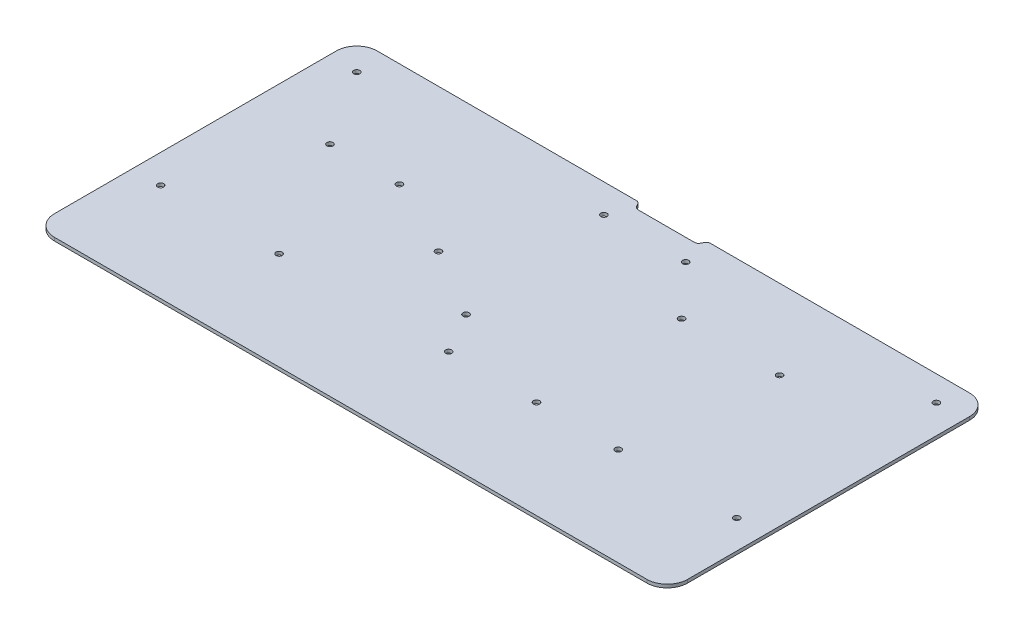
SolidWorks part; units mm, degrees
ref_plane "前视基准面" through (0, 0, 0) normal (0, 0, 1) x (1, 0, 0)
ref_plane "上视基准面" through (0, 0, 0) normal (0, 1, 0) x (1, 0, 0)
ref_plane "右视基准面" through (0, 0, 0) normal (1, 0, 0) x (0, 0, -1)
sketch "草图1" plane through (0, 0, 0) normal (0, 1, 0) x (1, 0, 0)
  line L0 (183.25, -128.5) -> (183.25, -131.5) construction
  line L1 (10, 0) -> (136.8844, 0)
  line L2 (0, -10) -> (0, -210) construction
  line L3 (10, -220) -> (300, -220) construction
  line L4 (310, -10) -> (310, -210) construction
  line L5 (28.75, -14.75) -> (47.25, -14.75) construction
  line L6 (28.75, -14.75) -> (28.75, -33.25) construction
  line L7 (28.75, -33.25) -> (47.25, -33.25) construction
  line L8 (173, -85) -> (173, 0) construction
  line L9 (173, -85) -> (310, -85) construction
  line L10 (190, -66) -> (190, 0) construction
  line L11 (215, -58) -> (215, 0) construction
  line L12 (241, -58) -> (241, 0) construction
  line L13 (247, -84) -> (247, 0) construction
  line L14 (222, -84) -> (222, 0) construction
  line L15 (0, -220) -> (310, 0) construction
  line L16 (241, -58) -> (310, -58) construction
  line L17 (247, -84) -> (310, -84) construction
  line L18 (215, -58) -> (310, -58) construction
  line L19 (222, -84) -> (310, -84) construction
  line L20 (190, -66) -> (310, -66) construction
  line L21 (310, -220) -> (0, 0) construction
  line L22 (141.1791, -3.5) -> (143.5, -3.5)
  line L23 (139.4291, -2.4682) -> (138.6344, -1.0318)
  line L24 (170.5709, -2.4682) -> (171.3656, -1.0318)
  line L25 (173.1156, 0) -> (300, 0)
  line L26 (155, -110) -> (155, -220) construction
  line L27 (47.25, -14.75) -> (47.25, -33.25) construction
  line L28 (28.75, -14.75) -> (47.25, -33.25) construction
  line L29 (28.75, -33.25) -> (47.25, -14.75) construction
  line L30 (52.75, -14.75) -> (71.25, -14.75) construction
  line L31 (52.75, -14.75) -> (52.75, -33.25) construction
  line L32 (52.75, -33.25) -> (71.25, -33.25) construction
  line L33 (71.25, -14.75) -> (71.25, -33.25) construction
  line L34 (52.75, -14.75) -> (71.25, -33.25) construction
  line L35 (52.75, -33.25) -> (71.25, -14.75) construction
  line L36 (76.75, -14.75) -> (95.25, -14.75) construction
  line L37 (76.75, -14.75) -> (76.75, -33.25) construction
  line L38 (76.75, -33.25) -> (95.25, -33.25) construction
  line L39 (95.25, -14.75) -> (95.25, -33.25) construction
  line L40 (76.75, -14.75) -> (95.25, -33.25) construction
  line L41 (76.75, -33.25) -> (95.25, -14.75) construction
  line L42 (100.75, -14.75) -> (119.25, -14.75) construction
  line L43 (100.75, -14.75) -> (100.75, -33.25) construction
  line L44 (100.75, -33.25) -> (119.25, -33.25) construction
  line L45 (119.25, -14.75) -> (119.25, -33.25) construction
  line L46 (100.75, -14.75) -> (119.25, -33.25) construction
  line L47 (100.75, -33.25) -> (119.25, -14.75) construction
  line L48 (188.75, -14.75) -> (207.25, -14.75) construction
  line L49 (188.75, -14.75) -> (188.75, -33.25) construction
  line L50 (188.75, -33.25) -> (207.25, -33.25) construction
  line L51 (207.25, -14.75) -> (207.25, -33.25) construction
  line L52 (188.75, -14.75) -> (207.25, -33.25) construction
  line L53 (188.75, -33.25) -> (207.25, -14.75) construction
  line L54 (212.75, -14.75) -> (231.25, -14.75) construction
  line L55 (212.75, -14.75) -> (212.75, -33.25) construction
  line L56 (212.75, -33.25) -> (231.25, -33.25) construction
  line L57 (231.25, -14.75) -> (231.25, -33.25) construction
  line L58 (212.75, -14.75) -> (231.25, -33.25) construction
  line L59 (212.75, -33.25) -> (231.25, -14.75) construction
  line L60 (236.75, -14.75) -> (255.25, -14.75) construction
  line L61 (236.75, -14.75) -> (236.75, -33.25) construction
  line L62 (236.75, -33.25) -> (255.25, -33.25) construction
  line L63 (255.25, -14.75) -> (255.25, -33.25) construction
  line L64 (236.75, -14.75) -> (255.25, -33.25) construction
  line L65 (236.75, -33.25) -> (255.25, -14.75) construction
  line L66 (260.75, -14.75) -> (279.25, -14.75) construction
  line L67 (260.75, -14.75) -> (260.75, -33.25) construction
  line L68 (260.75, -33.25) -> (279.25, -33.25) construction
  line L69 (279.25, -14.75) -> (279.25, -33.25) construction
  line L70 (260.75, -14.75) -> (279.25, -33.25) construction
  line L71 (260.75, -33.25) -> (279.25, -14.75) construction
  line L72 (183, -123) -> (197, -123) construction
  line L73 (183, -123) -> (183, -128.25) construction
  line L74 (183, -137) -> (197, -137) construction
  line L75 (197, -123) -> (197, -128.25) construction
  line L76 (183, -123) -> (197, -137) construction
  line L77 (183, -137) -> (197, -123) construction
  line L78 (183.25, -128.5) -> (183, -128.25) construction
  line L79 (183.25, -131.5) -> (183, -131.75) construction
  line L80 (196.75, -128.5) -> (196.75, -131.5) construction
  line L81 (196.75, -128.5) -> (197, -128.25) construction
  line L82 (196.75, -131.5) -> (197, -131.75) construction
  line L83 (183, -131.75) -> (183, -137) construction
  line L84 (197, -131.75) -> (197, -137) construction
  line L85 (31.25, -22.5) -> (31.25, -25.5) construction
  line L86 (31, -17) -> (45, -17) construction
  line L87 (31, -17) -> (31, -22.25) construction
  line L88 (31, -31) -> (45, -31) construction
  line L89 (45, -17) -> (45, -22.25) construction
  line L90 (31, -17) -> (45, -31) construction
  line L91 (31, -31) -> (45, -17) construction
  line L92 (31.25, -22.5) -> (31, -22.25) construction
  line L93 (31.25, -25.5) -> (31, -25.75) construction
  line L94 (44.75, -22.5) -> (44.75, -25.5) construction
  line L95 (44.75, -22.5) -> (45, -22.25) construction
  line L96 (44.75, -25.5) -> (45, -25.75) construction
  line L97 (31, -25.75) -> (31, -31) construction
  line L98 (45, -25.75) -> (45, -31) construction
  line L99 (55.25, -22.5) -> (55.25, -25.5) construction
  line L100 (55, -17) -> (69, -17) construction
  line L101 (55, -17) -> (55, -22.25) construction
  line L102 (55, -31) -> (69, -31) construction
  line L103 (69, -17) -> (69, -22.25) construction
  line L104 (55, -17) -> (69, -31) construction
  line L105 (55, -31) -> (69, -17) construction
  line L106 (55.25, -22.5) -> (55, -22.25) construction
  line L107 (55.25, -25.5) -> (55, -25.75) construction
  line L108 (68.75, -22.5) -> (68.75, -25.5) construction
  line L109 (68.75, -22.5) -> (69, -22.25) construction
  line L110 (68.75, -25.5) -> (69, -25.75) construction
  line L111 (55, -25.75) -> (55, -31) construction
  line L112 (69, -25.75) -> (69, -31) construction
  line L113 (79.25, -22.5) -> (79.25, -25.5) construction
  line L114 (79, -17) -> (93, -17) construction
  line L115 (79, -17) -> (79, -22.25) construction
  line L116 (79, -31) -> (93, -31) construction
  line L117 (93, -17) -> (93, -22.25) construction
  line L118 (79, -17) -> (93, -31) construction
  line L119 (79, -31) -> (93, -17) construction
  line L120 (79.25, -22.5) -> (79, -22.25) construction
  line L121 (79.25, -25.5) -> (79, -25.75) construction
  line L122 (92.75, -22.5) -> (92.75, -25.5) construction
  line L123 (92.75, -22.5) -> (93, -22.25) construction
  line L124 (92.75, -25.5) -> (93, -25.75) construction
  line L125 (79, -25.75) -> (79, -31) construction
  line L126 (93, -25.75) -> (93, -31) construction
  line L127 (103.25, -22.5) -> (103.25, -25.5) construction
  line L128 (103, -17) -> (117, -17) construction
  line L129 (103, -17) -> (103, -22.25) construction
  line L130 (103, -31) -> (117, -31) construction
  line L131 (117, -17) -> (117, -22.25) construction
  line L132 (103, -17) -> (117, -31) construction
  line L133 (103, -31) -> (117, -17) construction
  line L134 (103.25, -22.5) -> (103, -22.25) construction
  line L135 (103.25, -25.5) -> (103, -25.75) construction
  line L136 (116.75, -22.5) -> (116.75, -25.5) construction
  line L137 (116.75, -22.5) -> (117, -22.25) construction
  line L138 (116.75, -25.5) -> (117, -25.75) construction
  line L139 (103, -25.75) -> (103, -31) construction
  line L140 (117, -25.75) -> (117, -31) construction
  line L141 (191.25, -22.5) -> (191.25, -25.5) construction
  line L142 (191, -17) -> (205, -17) construction
  line L143 (191, -17) -> (191, -22.25) construction
  line L144 (191, -31) -> (205, -31) construction
  line L145 (205, -17) -> (205, -22.25) construction
  line L146 (191, -17) -> (205, -31) construction
  line L147 (191, -31) -> (205, -17) construction
  line L148 (191.25, -22.5) -> (191, -22.25) construction
  line L149 (191.25, -25.5) -> (191, -25.75) construction
  line L150 (204.75, -22.5) -> (204.75, -25.5) construction
  line L151 (204.75, -22.5) -> (205, -22.25) construction
  line L152 (204.75, -25.5) -> (205, -25.75) construction
  line L153 (191, -25.75) -> (191, -31) construction
  line L154 (205, -25.75) -> (205, -31) construction
  line L155 (215.25, -22.5) -> (215.25, -25.5) construction
  line L156 (215, -17) -> (229, -17) construction
  line L157 (215, -17) -> (215, -22.25) construction
  line L158 (215, -31) -> (229, -31) construction
  line L159 (229, -17) -> (229, -22.25) construction
  line L160 (215, -17) -> (229, -31) construction
  line L161 (215, -31) -> (229, -17) construction
  line L162 (215.25, -22.5) -> (215, -22.25) construction
  line L163 (215.25, -25.5) -> (215, -25.75) construction
  line L164 (228.75, -22.5) -> (228.75, -25.5) construction
  line L165 (228.75, -22.5) -> (229, -22.25) construction
  line L166 (228.75, -25.5) -> (229, -25.75) construction
  line L167 (215, -25.75) -> (215, -31) construction
  line L168 (229, -25.75) -> (229, -31) construction
  line L169 (239.25, -22.5) -> (239.25, -25.5) construction
  line L170 (239, -17) -> (253, -17) construction
  line L171 (239, -17) -> (239, -22.25) construction
  line L172 (239, -31) -> (253, -31) construction
  line L173 (253, -17) -> (253, -22.25) construction
  line L174 (239, -17) -> (253, -31) construction
  line L175 (239, -31) -> (253, -17) construction
  line L176 (239.25, -22.5) -> (239, -22.25) construction
  line L177 (239.25, -25.5) -> (239, -25.75) construction
  line L178 (252.75, -22.5) -> (252.75, -25.5) construction
  line L179 (252.75, -22.5) -> (253, -22.25) construction
  line L180 (252.75, -25.5) -> (253, -25.75) construction
  line L181 (239, -25.75) -> (239, -31) construction
  line L182 (253, -25.75) -> (253, -31) construction
  line L183 (263.25, -22.5) -> (263.25, -25.5) construction
  line L184 (263, -17) -> (277, -17) construction
  line L185 (263, -17) -> (263, -22.25) construction
  line L186 (263, -31) -> (277, -31) construction
  line L187 (277, -17) -> (277, -22.25) construction
  line L188 (263, -17) -> (277, -31) construction
  line L189 (263, -31) -> (277, -17) construction
  line L190 (263.25, -22.5) -> (263, -22.25) construction
  line L191 (263.25, -25.5) -> (263, -25.75) construction
  line L192 (276.75, -22.5) -> (276.75, -25.5) construction
  line L193 (276.75, -22.5) -> (277, -22.25) construction
  line L194 (276.75, -25.5) -> (277, -25.75) construction
  line L195 (263, -25.75) -> (263, -31) construction
  line L196 (277, -25.75) -> (277, -31) construction
  line L197 (259.25, -64.5) -> (259.25, -67.5) construction
  line L198 (259, -59) -> (273, -59) construction
  line L199 (259, -59) -> (259, -64.25) construction
  line L200 (259, -73) -> (273, -73) construction
  line L201 (273, -59) -> (273, -64.25) construction
  line L202 (259, -59) -> (273, -73) construction
  line L203 (259, -73) -> (273, -59) construction
  line L204 (259.25, -64.5) -> (259, -64.25) construction
  line L205 (259.25, -67.5) -> (259, -67.75) construction
  line L206 (272.75, -64.5) -> (272.75, -67.5) construction
  line L207 (272.75, -64.5) -> (273, -64.25) construction
  line L208 (272.75, -67.5) -> (273, -67.75) construction
  line L209 (259, -67.75) -> (259, -73) construction
  line L210 (273, -67.75) -> (273, -73) construction
  line L211 (240.25, -82.5) -> (240.25, -85.5) construction
  line L212 (240, -77) -> (254, -77) construction
  line L213 (240, -77) -> (240, -82.25) construction
  line L214 (240, -91) -> (254, -91) construction
  line L215 (254, -77) -> (254, -82.25) construction
  line L216 (240, -77) -> (254, -91) construction
  line L217 (240, -91) -> (254, -77) construction
  line L218 (240.25, -82.5) -> (240, -82.25) construction
  line L219 (240.25, -85.5) -> (240, -85.75) construction
  line L220 (253.75, -82.5) -> (253.75, -85.5) construction
  line L221 (253.75, -82.5) -> (254, -82.25) construction
  line L222 (253.75, -85.5) -> (254, -85.75) construction
  line L223 (240, -85.75) -> (240, -91) construction
  line L224 (254, -85.75) -> (254, -91) construction
  line L225 (234.25, -56.5) -> (234.25, -59.5) construction
  line L226 (234, -51) -> (248, -51) construction
  line L227 (234, -51) -> (234, -56.25) construction
  line L228 (234, -65) -> (248, -65) construction
  line L229 (248, -51) -> (248, -56.25) construction
  line L230 (234, -51) -> (248, -65) construction
  line L231 (234, -65) -> (248, -51) construction
  line L232 (234.25, -56.5) -> (234, -56.25) construction
  line L233 (234.25, -59.5) -> (234, -59.75) construction
  line L234 (247.75, -56.5) -> (247.75, -59.5) construction
  line L235 (247.75, -56.5) -> (248, -56.25) construction
  line L236 (247.75, -59.5) -> (248, -59.75) construction
  line L237 (234, -59.75) -> (234, -65) construction
  line L238 (248, -59.75) -> (248, -65) construction
  line L239 (215.25, -82.5) -> (215.25, -85.5) construction
  line L240 (215, -77) -> (229, -77) construction
  line L241 (215, -77) -> (215, -82.25) construction
  line L242 (215, -91) -> (229, -91) construction
  line L243 (229, -77) -> (229, -82.25) construction
  line L244 (215, -77) -> (229, -91) construction
  line L245 (215, -91) -> (229, -77) construction
  line L246 (215.25, -82.5) -> (215, -82.25) construction
  line L247 (215.25, -85.5) -> (215, -85.75) construction
  line L248 (228.75, -82.5) -> (228.75, -85.5) construction
  line L249 (228.75, -82.5) -> (229, -82.25) construction
  line L250 (228.75, -85.5) -> (229, -85.75) construction
  line L251 (215, -85.75) -> (215, -91) construction
  line L252 (229, -85.75) -> (229, -91) construction
  line L253 (29.25, -95.5) -> (29.25, -98.5) construction
  line L254 (29, -90) -> (43, -90) construction
  line L255 (29, -90) -> (29, -95.25) construction
  line L256 (29, -104) -> (43, -104) construction
  line L257 (43, -90) -> (43, -95.25) construction
  line L258 (29, -90) -> (43, -104) construction
  line L259 (29, -104) -> (43, -90) construction
  line L260 (29.25, -95.5) -> (29, -95.25) construction
  line L261 (29.25, -98.5) -> (29, -98.75) construction
  line L262 (42.75, -95.5) -> (42.75, -98.5) construction
  line L263 (42.75, -95.5) -> (43, -95.25) construction
  line L264 (42.75, -98.5) -> (43, -98.75) construction
  line L265 (29, -98.75) -> (29, -104) construction
  line L266 (43, -98.75) -> (43, -104) construction
  line L267 (51.25, -78.5) -> (51.25, -81.5) construction
  line L268 (51, -73) -> (65, -73) construction
  line L269 (51, -73) -> (51, -78.25) construction
  line L270 (51, -87) -> (65, -87) construction
  line L271 (65, -73) -> (65, -78.25) construction
  line L272 (51, -73) -> (65, -87) construction
  line L273 (51, -87) -> (65, -73) construction
  line L274 (51.25, -78.5) -> (51, -78.25) construction
  line L275 (51.25, -81.5) -> (51, -81.75) construction
  line L276 (64.75, -78.5) -> (64.75, -81.5) construction
  line L277 (64.75, -78.5) -> (65, -78.25) construction
  line L278 (64.75, -81.5) -> (65, -81.75) construction
  line L279 (51, -81.75) -> (51, -87) construction
  line L280 (65, -81.75) -> (65, -87) construction
  line L281 (77.25, -75.5) -> (77.25, -78.5) construction
  line L282 (77, -70) -> (91, -70) construction
  line L283 (77, -70) -> (77, -75.25) construction
  line L284 (77, -84) -> (91, -84) construction
  line L285 (91, -70) -> (91, -75.25) construction
  line L286 (77, -70) -> (91, -84) construction
  line L287 (77, -84) -> (91, -70) construction
  line L288 (77.25, -75.5) -> (77, -75.25) construction
  line L289 (77.25, -78.5) -> (77, -78.75) construction
  line L290 (90.75, -75.5) -> (90.75, -78.5) construction
  line L291 (90.75, -75.5) -> (91, -75.25) construction
  line L292 (90.75, -78.5) -> (91, -78.75) construction
  line L293 (77, -78.75) -> (77, -84) construction
  line L294 (91, -78.75) -> (91, -84) construction
  line L295 (82.25, -51.5) -> (82.25, -54.5) construction
  line L296 (82, -46) -> (96, -46) construction
  line L297 (82, -46) -> (82, -51.25) construction
  line L298 (82, -60) -> (96, -60) construction
  line L299 (96, -46) -> (96, -51.25) construction
  line L300 (82, -46) -> (96, -60) construction
  line L301 (82, -60) -> (96, -46) construction
  line L302 (82.25, -51.5) -> (82, -51.25) construction
  line L303 (82.25, -54.5) -> (82, -54.75) construction
  line L304 (95.75, -51.5) -> (95.75, -54.5) construction
  line L305 (95.75, -51.5) -> (96, -51.25) construction
  line L306 (95.75, -54.5) -> (96, -54.75) construction
  line L307 (82, -54.75) -> (82, -60) construction
  line L308 (96, -54.75) -> (96, -60) construction
  line L309 (99.25, -88.5) -> (99.25, -91.5) construction
  line L310 (99, -83) -> (113, -83) construction
  line L311 (99, -83) -> (99, -88.25) construction
  line L312 (99, -97) -> (113, -97) construction
  line L313 (113, -83) -> (113, -88.25) construction
  line L314 (99, -83) -> (113, -97) construction
  line L315 (99, -97) -> (113, -83) construction
  line L316 (99.25, -88.5) -> (99, -88.25) construction
  line L317 (99.25, -91.5) -> (99, -91.75) construction
  line L318 (112.75, -88.5) -> (112.75, -91.5) construction
  line L319 (112.75, -88.5) -> (113, -88.25) construction
  line L320 (112.75, -91.5) -> (113, -91.75) construction
  line L321 (99, -91.75) -> (99, -97) construction
  line L322 (113, -91.75) -> (113, -97) construction
  line L323 (208.25, -56.5) -> (208.25, -59.5) construction
  line L324 (208, -51) -> (222, -51) construction
  line L325 (208, -51) -> (208, -56.25) construction
  line L326 (208, -65) -> (222, -65) construction
  line L327 (222, -51) -> (222, -56.25) construction
  line L328 (208, -51) -> (222, -65) construction
  line L329 (208, -65) -> (222, -51) construction
  line L330 (208.25, -56.5) -> (208, -56.25) construction
  line L331 (208.25, -59.5) -> (208, -59.75) construction
  line L332 (221.75, -56.5) -> (221.75, -59.5) construction
  line L333 (221.75, -56.5) -> (222, -56.25) construction
  line L334 (221.75, -59.5) -> (222, -59.75) construction
  line L335 (208, -59.75) -> (208, -65) construction
  line L336 (222, -59.75) -> (222, -65) construction
  line L337 (183.25, -64.5) -> (183.25, -67.5) construction
  line L338 (183, -59) -> (197, -59) construction
  line L339 (183, -59) -> (183, -64.25) construction
  line L340 (183, -73) -> (197, -73) construction
  line L341 (197, -59) -> (197, -64.25) construction
  line L342 (183, -59) -> (197, -73) construction
  line L343 (183, -73) -> (197, -59) construction
  line L344 (183.25, -64.5) -> (183, -64.25) construction
  line L345 (183.25, -67.5) -> (183, -67.75) construction
  line L346 (196.75, -64.5) -> (196.75, -67.5) construction
  line L347 (196.75, -64.5) -> (197, -64.25) construction
  line L348 (196.75, -67.5) -> (197, -67.75) construction
  line L349 (183, -67.75) -> (183, -73) construction
  line L350 (197, -67.75) -> (197, -73) construction
  line L351 (191.25, -88.5) -> (191.25, -91.5) construction
  line L352 (191, -83) -> (205, -83) construction
  line L353 (191, -83) -> (191, -88.25) construction
  line L354 (191, -97) -> (205, -97) construction
  line L355 (205, -83) -> (205, -88.25) construction
  line L356 (191, -83) -> (205, -97) construction
  line L357 (191, -97) -> (205, -83) construction
  line L358 (191.25, -88.5) -> (191, -88.25) construction
  line L359 (191.25, -91.5) -> (191, -91.75) construction
  line L360 (204.75, -88.5) -> (204.75, -91.5) construction
  line L361 (204.75, -88.5) -> (205, -88.25) construction
  line L362 (204.75, -91.5) -> (205, -91.75) construction
  line L363 (191, -91.75) -> (191, -97) construction
  line L364 (205, -91.75) -> (205, -97) construction
  line L365 (166.25, -83.5) -> (166.25, -86.5) construction
  line L366 (166, -78) -> (180, -78) construction
  line L367 (166, -78) -> (166, -83.25) construction
  line L368 (166, -92) -> (180, -92) construction
  line L369 (180, -78) -> (180, -83.25) construction
  line L370 (166, -78) -> (180, -92) construction
  line L371 (166, -92) -> (180, -78) construction
  line L372 (166.25, -83.5) -> (166, -83.25) construction
  line L373 (166.25, -86.5) -> (166, -86.75) construction
  line L374 (179.75, -83.5) -> (179.75, -86.5) construction
  line L375 (179.75, -83.5) -> (180, -83.25) construction
  line L376 (179.75, -86.5) -> (180, -86.75) construction
  line L377 (166, -86.75) -> (166, -92) construction
  line L378 (180, -86.75) -> (180, -92) construction
  line L379 (107.25, -128.5) -> (107.25, -131.5) construction
  line L380 (107, -123) -> (121, -123) construction
  line L381 (107, -123) -> (107, -128.25) construction
  line L382 (107, -137) -> (121, -137) construction
  line L383 (121, -123) -> (121, -128.25) construction
  line L384 (107, -123) -> (121, -137) construction
  line L385 (107, -137) -> (121, -123) construction
  line L386 (107.25, -128.5) -> (107, -128.25) construction
  line L387 (107.25, -131.5) -> (107, -131.75) construction
  line L388 (120.75, -128.5) -> (120.75, -131.5) construction
  line L389 (120.75, -128.5) -> (121, -128.25) construction
  line L390 (120.75, -131.5) -> (121, -131.75) construction
  line L391 (107, -131.75) -> (107, -137) construction
  line L392 (121, -131.75) -> (121, -137) construction
  line L393 (138.25, -136.5) -> (138.25, -139.5) construction
  line L394 (138, -131) -> (152, -131) construction
  line L395 (138, -131) -> (138, -136.25) construction
  line L396 (138, -145) -> (152, -145) construction
  line L397 (152, -131) -> (152, -136.25) construction
  line L398 (138, -131) -> (152, -145) construction
  line L399 (138, -145) -> (152, -131) construction
  line L400 (138.25, -136.5) -> (138, -136.25) construction
  line L401 (138.25, -139.5) -> (138, -139.75) construction
  line L402 (151.75, -136.5) -> (151.75, -139.5) construction
  line L403 (151.75, -136.5) -> (152, -136.25) construction
  line L404 (151.75, -139.5) -> (152, -139.75) construction
  line L405 (138, -139.75) -> (138, -145) construction
  line L406 (152, -139.75) -> (152, -145) construction
  line L407 (166.5, -3.5) -> (168.8209, -3.5)
  line L409 (143.5, -3.5) -> (143.5, -55.5) construction
  line L410 (143.5, -55.5) -> (166.5, -55.5) construction
  line L411 (166.5, -3.5) -> (166.5, -55.5) construction
  line L412 (143.5, -3.5) -> (166.5, -55.5) construction
  line L413 (143.5, -55.5) -> (166.5, -3.5) construction
  line L414 (10, -158) -> (300, -158)
  line L415 (0, -158) -> (0, -210) construction
  line L416 (310, -148) -> (310, -10)
  line L417 (0, -148) -> (0, -10)
  line L418 (143.5, -3.5) -> (166.5, -3.5)
  arc A0 (10, 0) -> (0, -10) centre (10, -10) ccw
  arc A1 (0, -210) -> (10, -220) centre (10, -210) ccw construction
  arc A2 (300, -220) -> (310, -210) centre (300, -210) ccw construction
  arc A3 (300, 0) -> (310, -10) centre (300, -10) cw
  circle A8 centre (173, -85) radius 11 construction
  circle A9 centre (190, -66) radius 11 construction
  circle A11 centre (215, -58) radius 11 construction
  circle A12 centre (222, -84) radius 11 construction
  circle A13 centre (247, -84) radius 11 construction
  circle A14 centre (241, -58) radius 11 construction
  circle A15 centre (14, -14) radius 1.5
  circle A16 centre (14, -206) radius 1.5 construction
  circle A17 centre (296, -206) radius 1.5 construction
  circle A18 centre (296, -12.2857) radius 1.5
  arc A19 (173.1156, 0) -> (171.3656, -1.0318) centre (173.1156, -2) ccw
  arc A20 (170.5709, -2.4682) -> (168.8209, -3.5) centre (168.8209, -1.5) cw
  arc A21 (141.1791, -3.5) -> (139.4291, -2.4682) centre (141.1791, -1.5) cw
  arc A22 (136.8844, 0) -> (138.6344, -1.0318) centre (136.8844, -2) cw
  circle A24 centre (198, -90) radius 11 construction
  circle A25 centre (114, -130) radius 13.5 construction
  circle A26 centre (190, -130) radius 13.5 construction
  circle A27 centre (155, -206) radius 1.5 construction
  circle A28 centre (175, -14) radius 1.5
  circle A29 centre (145, -138) radius 11 construction
  circle A30 centre (106, -90) radius 11 construction
  circle A31 centre (84, -77) radius 11 construction
  circle A32 centre (58, -80) radius 11 construction
  circle A33 centre (36, -97) radius 11 construction
  circle A34 centre (89, -53) radius 11 construction
  circle A35 centre (266, -66) radius 11 construction
  circle A36 centre (110, -24) radius 4.5 construction
  circle A37 centre (86, -24) radius 4.5 construction
  circle A38 centre (62, -24) radius 4.5 construction
  circle A39 centre (38, -24) radius 4.5 construction
  circle A40 centre (198, -24) radius 4.5 construction
  circle A41 centre (222, -24) radius 4.5 construction
  circle A42 centre (246, -24) radius 4.5 construction
  circle A43 centre (270, -24) radius 4.5 construction
  circle A48 centre (135, -14) radius 1.5
  circle A51 centre (296, -110) radius 1.5
  circle A52 centre (14, -110) radius 1.5
  circle A53 centre (155, -110) radius 1.5
  circle A54 centre (72, -110) radius 1.5
  circle A55 centre (72, -168.9032) radius 1.5 construction
  circle A56 centre (72, -51.0968) radius 1.5
  circle A57 centre (42, -168.9032) radius 1.5 construction
  circle A58 centre (102, -168.9032) radius 1.5 construction
  circle A59 centre (238, -110) radius 1.5
  circle A60 centre (238, -168.9032) radius 1.5 construction
  circle A61 centre (268, -168.9032) radius 1.5 construction
  circle A62 centre (208, -168.9032) radius 1.5 construction
  circle A63 centre (246, -39) radius 1.5
  circle A64 centre (198, -39) radius 1.5
  circle A65 centre (110, -70) radius 1.5
  circle A66 centre (38, -51.0968) radius 1.5
  circle A67 centre (198, -110) radius 1.5
  circle A68 centre (143.5, -90) radius 1.5
  arc A69 (310, -148) -> (300, -158) centre (300, -148) cw
  arc A70 (10, -158) -> (0, -148) centre (10, -148) cw
  point P8 (0, 0)
  point P12 (0, -220)
  point P15 (310, -220)
  point P18 (310, 0)
  point P70 (171.9365, 0)
  point P73 (170, -3.5)
  point P76 (140, -3.5)
  point P79 (138.0635, 0)
  point P147 (190, -130)
  point P152 (155, -29.5)
  point P155 (183.25, -130)
  point P160 (196.75, -130)
  point P163 (38, -24)
  point P170 (31.25, -24)
  point P175 (44.75, -24)
  point P180 (62, -24)
  point P187 (55.25, -24)
  point P192 (68.75, -24)
  point P196 (86, -24)
  point P203 (79.25, -24)
  point P208 (92.75, -24)
  point P213 (110, -24)
  point P220 (103.25, -24)
  point P225 (116.75, -24)
  point P229 (198, -24)
  point P236 (191.25, -24)
  point P241 (204.75, -24)
  point P245 (222, -24)
  point P252 (215.25, -24)
  point P257 (228.75, -24)
  point P261 (246, -24)
  point P268 (239.25, -24)
  point P273 (252.75, -24)
  point P277 (270, -24)
  point P284 (263.25, -24)
  point P289 (276.75, -24)
  point P293 (266, -66)
  point P300 (259.25, -66)
  point P305 (272.75, -66)
  point P310 (247, -84)
  point P317 (240.25, -84)
  point P322 (253.75, -84)
  point P326 (241, -58)
  point P333 (234.25, -58)
  point P338 (247.75, -58)
  point P342 (222, -84)
  point P349 (215.25, -84)
  point P354 (228.75, -84)
  point P358 (36, -97)
  point P365 (29.25, -97)
  point P370 (42.75, -97)
  point P374 (58, -80)
  point P381 (51.25, -80)
  point P386 (64.75, -80)
  point P389 (310, -158)
  point P390 (84, -77)
  point P397 (77.25, -77)
  point P402 (90.75, -77)
  point P407 (89, -53)
  point P414 (82.25, -53)
  point P419 (95.75, -53)
  point P423 (106, -90)
  point P430 (99.25, -90)
  point P435 (112.75, -90)
  point P439 (215, -58)
  point P446 (208.25, -58)
  point P451 (221.75, -58)
  point P455 (190, -66)
  point P462 (183.25, -66)
  point P467 (196.75, -66)
  point P471 (198, -90)
  point P478 (191.25, -90)
  point P483 (204.75, -90)
  point P492 (173, -85)
  point P499 (166.25, -85)
  point P504 (179.75, -85)
  point P508 (114, -130)
  point P515 (107.25, -130)
  point P520 (120.75, -130)
  point P524 (145, -138)
  point P531 (138.25, -138)
  point P536 (151.75, -138)
  dimension "D3" = 10
  dimension "D7" = 90
  dimension "D10" = 22
  dimension "D15" = 53
  dimension "D16" = 22
  dimension "D19" = 22
  dimension "D20" = 22
  dimension "D21" = 22
  dimension "D22" = 84
  dimension "D23" = 22
  dimension "D24" = 22
  dimension "D32" = 22
  dimension "D34" = 3
  dimension "D37" = 3
  dimension "D40" = 3
  dimension "D43" = 3
  dimension "D47" = 3.5
  dimension "D50" = 140
  dimension "D51" = 2
  dimension "D52" = 90
  dimension "D54" = 27
  dimension "D56" = 27
  dimension "D59" = 3
  dimension "D61" = 14
  dimension "D62" = 3
  dimension "D64" = 22
  dimension "D8" = 22
  dimension "D9" = 22
  dimension "D11" = 22
  dimension "D12" = 22
  dimension "D13" = 22
  dimension "D76" = 9
  dimension "D84" = 9
  dimension "D86" = 3
  dimension "D89" = 18.5
  dimension "D92" = 18.5
  dimension "D95" = 18.5
  dimension "D98" = 3
  dimension "D101" = 18.5
  dimension "D103" = 18.5
  dimension "D87" = 3
  dimension "D301" = 3
  dimension "D302" = 3
  dimension "D304" = 3
  dimension "D305" = 3
  dimension "D306" = 3
  dimension "D308" = 3
  dimension "D310" = 3
  dimension "D312" = 3
  dimension "D313" = 3
  dimension "D314" = 3
  dimension "D317" = 3
  dimension "D319" = 3
  dimension "D321" = 3
  dimension "D323" = 3
  dimension "D324" = 3
  dimension "D325" = 3
  dimension "D327" = 10
  dimension "D1" = 220
  dimension "D2" = 310
  dimension "D14" = 89
  dimension "D17" = 85
  dimension "D18" = 137
  dimension "D25" = 66
  dimension "D26" = 120
  dimension "D27" = 36
  dimension "D28" = 58
  dimension "D29" = 95
  dimension "D30" = 88
  dimension "D31" = 69
  dimension "D33" = 63
  dimension "D35" = 14
  dimension "D36" = 14
  dimension "D38" = 14
  dimension "D39" = 14
  dimension "D41" = 14
  dimension "D42" = 14
  dimension "D44" = 14
  dimension "D45" = 12.2857
  dimension "D46" = 4
  dimension "D48" = 30
  dimension "D49" = 4
  dimension "D53" = 112
  dimension "D55" = 114
  dimension "D57" = 90
  dimension "D58" = 120
  dimension "D60" = 14
  dimension "D63" = 135
  dimension "D65" = 82
  dimension "D66" = 145
  dimension "D67" = 97
  dimension "D68" = 80
  dimension "D69" = 58
  dimension "D70" = 84
  dimension "D71" = 77
  dimension "D72" = 90
  dimension "D73" = 106
  dimension "D74" = 44
  dimension "D75" = 66
  dimension "D78" = 24
  dimension "D79" = 110
  dimension "D80" = 24
  dimension "D82" = 24
  dimension "D83" = 24
  dimension "D85" = 40
  dimension "D88" = 18.5
  dimension "D90" = 18.5
  dimension "D91" = 18.5
  dimension "D93" = 18.5
  dimension "D94" = 18.5
  dimension "D96" = 18.5
  dimension "D97" = 18.5
  dimension "D99" = 14
  dimension "D100" = 135
  dimension "D102" = 18.5
  dimension "D104" = 18.5
  dimension "D105" = 18.5
  dimension "D106" = 18.5
  dimension "D107" = 14
  dimension "D108" = 14
  dimension "D109" = 0.25
  dimension "D110" = 3
  dimension "D111" = 135
  dimension "D112" = 3
  dimension "D113" = 0.25
  dimension "D114" = 135
  dimension "D115" = 14
  dimension "D116" = 14
  dimension "D117" = 0.25
  dimension "D118" = 3
  dimension "D119" = 135
  dimension "D120" = 3
  dimension "D121" = 0.25
  dimension "D122" = 135
  dimension "D123" = 14
  dimension "D124" = 14
  dimension "D125" = 0.25
  dimension "D126" = 3
  dimension "D127" = 135
  dimension "D128" = 3
  dimension "D129" = 0.25
  dimension "D130" = 135
  dimension "D131" = 14
  dimension "D132" = 14
  dimension "D133" = 0.25
  dimension "D134" = 3
  dimension "D135" = 135
  dimension "D136" = 3
  dimension "D137" = 0.25
  dimension "D138" = 135
  dimension "D139" = 14
  dimension "D140" = 14
  dimension "D141" = 0.25
  dimension "D142" = 3
  dimension "D143" = 135
  dimension "D144" = 3
  dimension "D145" = 0.25
  dimension "D146" = 135
  dimension "D147" = 14
  dimension "D148" = 14
  dimension "D149" = 0.25
  dimension "D150" = 3
  dimension "D151" = 135
  dimension "D152" = 3
  dimension "D153" = 0.25
  dimension "D154" = 135
  dimension "D155" = 14
  dimension "D156" = 14
  dimension "D157" = 0.25
  dimension "D158" = 3
  dimension "D159" = 135
  dimension "D160" = 3
  dimension "D161" = 0.25
  dimension "D162" = 135
  dimension "D163" = 14
  dimension "D164" = 14
  dimension "D165" = 0.25
  dimension "D166" = 3
  dimension "D167" = 135
  dimension "D168" = 3
  dimension "D169" = 0.25
  dimension "D170" = 135
  dimension "D171" = 14
  dimension "D172" = 14
  dimension "D173" = 0.25
  dimension "D174" = 3
  dimension "D175" = 135
  dimension "D176" = 3
  dimension "D177" = 0.25
  dimension "D178" = 135
  dimension "D179" = 14
  dimension "D180" = 14
  dimension "D181" = 0.25
  dimension "D182" = 3
  dimension "D183" = 135
  dimension "D184" = 3
  dimension "D185" = 0.25
  dimension "D186" = 135
  dimension "D187" = 14
  dimension "D188" = 14
  dimension "D189" = 0.25
  dimension "D190" = 3
  dimension "D191" = 135
  dimension "D192" = 3
  dimension "D193" = 0.25
  dimension "D194" = 135
  dimension "D195" = 14
  dimension "D196" = 14
  dimension "D197" = 0.25
  dimension "D198" = 3
  dimension "D199" = 135
  dimension "D200" = 3
  dimension "D201" = 0.25
  dimension "D202" = 135
  dimension "D203" = 14
  dimension "D204" = 14
  dimension "D205" = 0.25
  dimension "D206" = 3
  dimension "D207" = 135
  dimension "D208" = 3
  dimension "D209" = 0.25
  dimension "D210" = 135
  dimension "D211" = 14
  dimension "D212" = 14
  dimension "D213" = 0.25
  dimension "D214" = 3
  dimension "D215" = 135
  dimension "D216" = 3
  dimension "D217" = 0.25
  dimension "D218" = 135
  dimension "D219" = 14
  dimension "D220" = 14
  dimension "D221" = 0.25
  dimension "D222" = 3
  dimension "D223" = 135
  dimension "D224" = 3
  dimension "D225" = 0.25
  dimension "D226" = 135
  dimension "D227" = 14
  dimension "D228" = 14
  dimension "D229" = 0.25
  dimension "D230" = 3
  dimension "D231" = 135
  dimension "D232" = 3
  dimension "D233" = 0.25
  dimension "D234" = 135
  dimension "D235" = 14
  dimension "D236" = 14
  dimension "D237" = 0.25
  dimension "D238" = 3
  dimension "D239" = 135
  dimension "D240" = 3
  dimension "D241" = 0.25
  dimension "D242" = 135
  dimension "D243" = 14
  dimension "D244" = 14
  dimension "D245" = 0.25
  dimension "D246" = 3
  dimension "D247" = 135
  dimension "D248" = 3
  dimension "D249" = 0.25
  dimension "D250" = 135
  dimension "D251" = 14
  dimension "D252" = 14
  dimension "D253" = 0.25
  dimension "D254" = 3
  dimension "D255" = 135
  dimension "D256" = 3
  dimension "D257" = 0.25
  dimension "D258" = 135
  dimension "D259" = 14
  dimension "D260" = 14
  dimension "D261" = 0.25
  dimension "D262" = 3
  dimension "D263" = 135
  dimension "D264" = 3
  dimension "D265" = 0.25
  dimension "D266" = 135
  dimension "D267" = 14
  dimension "D268" = 14
  dimension "D269" = 0.25
  dimension "D270" = 3
  dimension "D271" = 135
  dimension "D272" = 3
  dimension "D273" = 0.25
  dimension "D274" = 135
  dimension "D275" = 14
  dimension "D276" = 14
  dimension "D277" = 0.25
  dimension "D278" = 3
  dimension "D279" = 135
  dimension "D280" = 3
  dimension "D281" = 0.25
  dimension "D282" = 135
  dimension "D283" = 14
  dimension "D284" = 14
  dimension "D285" = 0.25
  dimension "D286" = 3
  dimension "D287" = 135
  dimension "D288" = 3
  dimension "D289" = 0.25
  dimension "D290" = 135
  dimension "D291" = 14
  dimension "D292" = 14
  dimension "D293" = 0.25
  dimension "D294" = 3
  dimension "D295" = 135
  dimension "D296" = 3
  dimension "D297" = 0.25
  dimension "D298" = 135
  dimension "D299" = 23
  dimension "D300" = 52
  dimension "D303" = 72
  dimension "D307" = 30
  dimension "D309" = 30
  dimension "D311" = 72
  dimension "D315" = 30
  dimension "D316" = 30
  dimension "D318" = 15
  dimension "D320" = 15
  dimension "D322" = 46
  dimension "D326" = 158
  dimension "D77" = 4
  dimension "D81" = 4
extrude "凸台-拉伸1" add sketch "草图1" along normal blind 1.6
